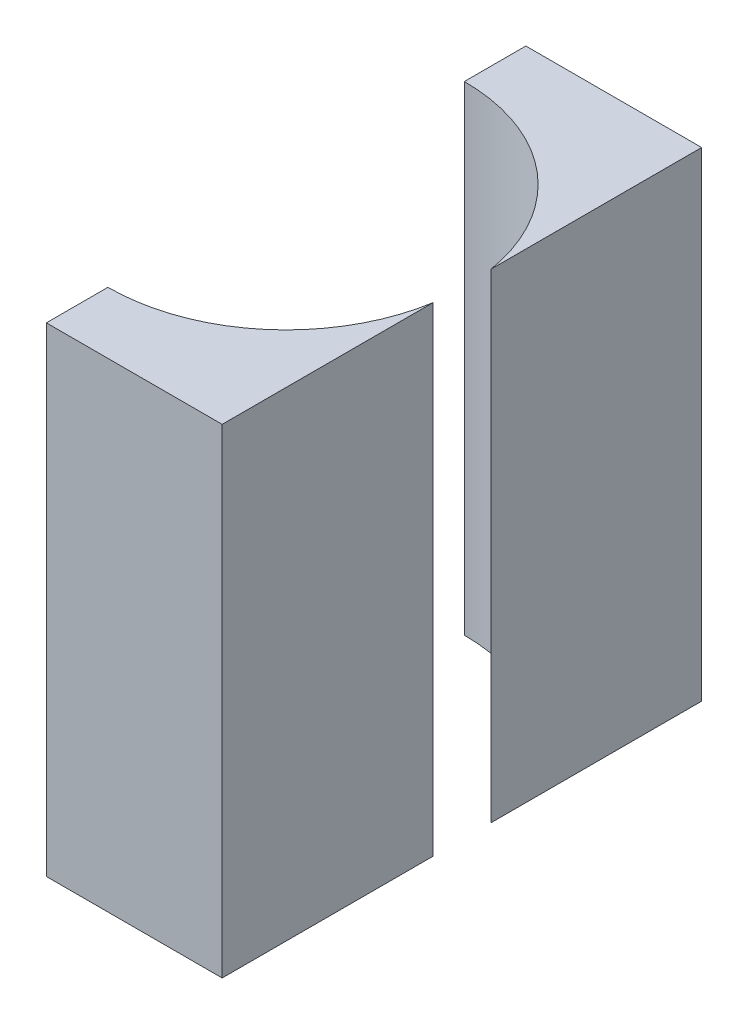
SolidWorks part; units mm, degrees
ref_plane "Front Plane" through (0, 0, 0) normal (0, 0, 1) x (1, 0, 0)
ref_plane "Top Plane" through (0, 0, 0) normal (0, 1, 0) x (1, 0, 0)
ref_plane "Right Plane" through (0, 0, 0) normal (1, 0, 0) x (0, 0, -1)
sketch "Sketch1" plane through (0, 86.6691, 0) normal (0, 1, 0) x (1, 0, 0)
  line L0 (245.7875, 7.2467) -> (234.7875, 7.2467)
  line L1 (234.7875, 7.2467) -> (234.7875, 11.0967)
  line L2 (234.8652, 22.2467) -> (-49765.1348, 22.2467) construction
  line L3 (245.7875, 37.2467) -> (234.7875, 37.2467)
  line L4 (234.7875, 37.2467) -> (234.7875, 33.3967)
  line L5 (245.7875, 7.2467) -> (245.7875, 37.2467)
  circle A0 centre (234.7875, 22.2467) radius 11 construction
  circle A1 centre (234.7875, 22.2467) radius 11
  circle A2 centre (234.7875, 22.2467) radius 11.15
  line M7 (245.7875, 33.2467) -> (245.7875, 11.2467)
  dimension "D1" = 0.15
extrude "Boss-Extrude1" add sketch "Sketch1" against normal up to surface (30 mm away) contours A2 L1 L0 L5 M7 | A2 L5 L3 L4 M7
